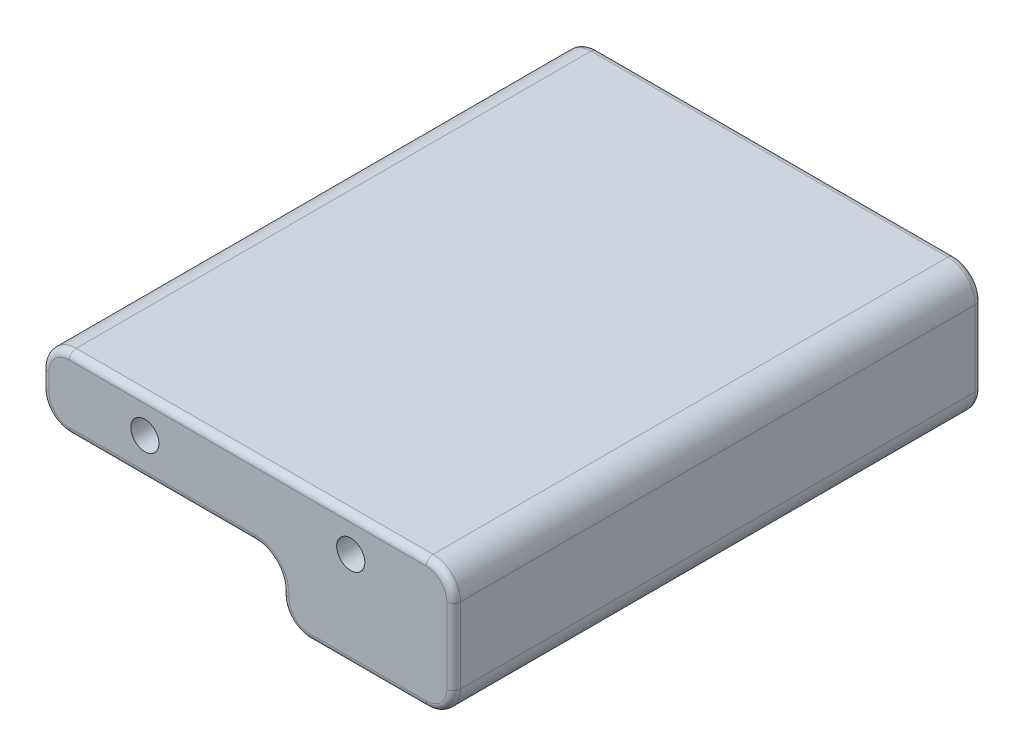
SolidWorks part; units mm, degrees
material "ABS"
ref_plane "前视基准面" through (0, 0, 0) normal (0, 0, 1) x (1, 0, 0)
ref_plane "上视基准面" through (0, 0, 0) normal (0, 1, 0) x (1, 0, 0)
ref_plane "右视基准面" through (0, 0, 0) normal (1, 0, 0) x (0, 0, -1)
other "Configuration Table"
sketch "草图1" plane through (0, 0, 0) normal (0, 0, 1) x (1, 0, 0)
  line L0 (30, 10.5) -> (30, 0) construction
  line L1 (0, 0) -> (60, 0)
  line L2 (0, 0) -> (0, 10.5)
  line L3 (0, 10.5) -> (60, 10.5)
  line L4 (60, 0) -> (60, 10.5)
  circle A0 centre (15, 5.5) radius 1.55
  circle A1 centre (45, 5.5) radius 1.55
  dimension "D5" = 3.1
  dimension "D6" = 3.1
  dimension "D1" = 60
  dimension "D2" = 10.5
  dimension "D3" = 5
  dimension "D4" = 5
  dimension "D7" = 15
  dimension "D8" = 15
extrude "凸台-拉伸1" add sketch "草图1" along normal blind 77
sketch "草图2" plane through (0, 0, 0) normal (0, -1, 0) x (1, 0, 0)
  line L0 (0, 0) -> (60, 0) construction
  line L1 (60, 77) -> (35, 77)
  line L2 (60, 77) -> (60, 0)
  line L3 (60, 0) -> (35, 0)
  line L4 (35, 77) -> (35, 0)
  dimension "D1" = 25
extrude "凸台-拉伸2" add sketch "草图2" along normal blind 8.5
fillet "圆角2" radius 4 6 edges at (35, -8.5, 38.5) (35, 0, 38.5) (60, -8.5, 38.5) (60, 10.5, 38.5) (0, 0, 38.5) (0, 10.5, 38.5)
sketch "草图3" plane through (0, 0, 0) normal (0, -1, 0) x (1, 0, 0)
  line L0 (0, 38.5) -> (31, 38.5) construction
  line L5 (31, 0) -> (31, 77) construction
  line L6 (0, 0) -> (0, 77) construction
  circle A0 centre (11.15, 63.5) radius 1.55
  circle A1 centre (11.15, 13.5) radius 1.55
  circle A2 centre (25.15, 63.5) radius 1.55
  circle A3 centre (25.15, 13.5) radius 1.55
  dimension "D5" = 3.1
  dimension "D6" = 3.1
  dimension "D7" = 3.1
  dimension "D8" = 3.1
  dimension "D1" = 11.15
  dimension "D2" = 11.15
  dimension "D3" = 14
  dimension "D4" = 14
  dimension "D9" = 25
  dimension "D10" = 25
  dimension "D11" = 25
  dimension "D12" = 25
extrude "切除-拉伸1" cut sketch "草图3" against normal blind 8
sketch "草图4" plane through (0, 0, 0) normal (0, 0, -1) x (-1, 0, 0)
  circle A0 centre (-45, 5.5) radius 2.05
  circle A1 centre (-15, 5.5) radius 2.05
  dimension "D1" = 4.1
  dimension "D2" = 4.1
extrude "切除-拉伸2" cut sketch "草图4" against normal blind 5
sketch "草图5" plane through (0, 0, 77) normal (0, 0, 1) x (1, 0, 0)
  circle A0 centre (15, 5.5) radius 2.05
  circle A1 centre (45, 5.5) radius 2.05
  dimension "D1" = 4.1
  dimension "D2" = 4.1
extrude "切除-拉伸3" cut sketch "草图5" against normal blind 5
fillet "圆角3" radius 1 24 edges at (58.8284, -7.3284, 0) (60, 1, 0) (58.8284, 9.3284, 0) (30, 10.5, 0) (1.1716, 9.3284, 0) (0, 5.25, 0) (1.1716, 1.1716, 0) (17.5, 0, 0) (33.8284, -1.1716, 0) (35, -4.25, 0) (36.1716, -7.3284, 0) (47.5, -8.5, 0) (33.8284, -1.1716, 77) (17.5, 0, 77) (1.1716, 1.1716, 77) (0, 5.25, 77) (1.1716, 9.3284, 77) (30, 10.5, 77) (58.8284, 9.3284, 77) (60, 1, 77) (58.8284, -7.3284, 77) (47.5, -8.5, 77) (36.1716, -7.3284, 77) (35, -4.25, 77)
sketch "草图6" plane through (0, 0, 0) normal (0, -1, 0) x (1, 0, 0)
  circle A0 centre (11.15, 63.5) radius 2.05
  circle A1 centre (25.15, 63.5) radius 2.05
  circle A2 centre (25.15, 13.5) radius 2.05
  circle A3 centre (11.15, 13.5) radius 2.05
  dimension "D1" = 4.1
  dimension "D2" = 4.1
  dimension "D3" = 4.1
  dimension "D4" = 4.1
extrude "切除-拉伸4" cut sketch "草图6" against normal blind 5
